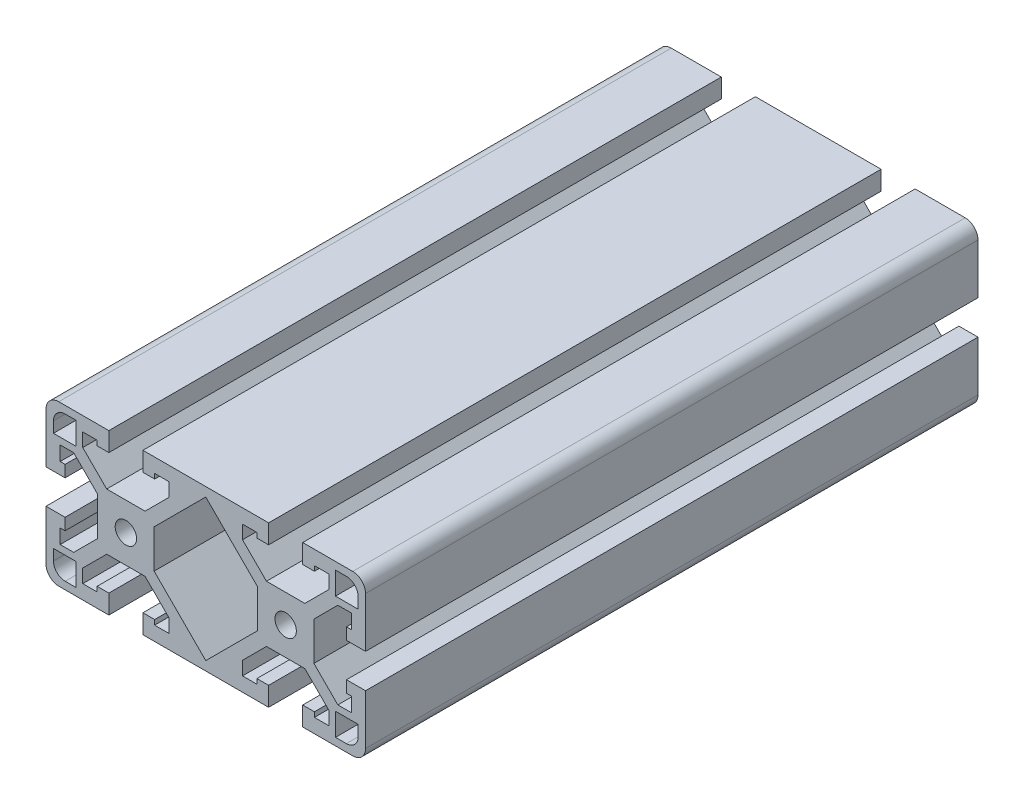
SolidWorks part; units mm, degrees
material "6061 Alloy"
ref_plane "Front Plane" through (0, 0, 0) normal (0, 0, 1) x (1, 0, 0)
ref_plane "Top Plane" through (0, 0, 0) normal (0, 1, 0) x (1, 0, 0)
ref_plane "Right Plane" through (0, 0, 0) normal (1, 0, 0) x (0, 0, -1)
sketch "Sketch1" plane through (0, 0, 0) normal (0, 0, 1) x (1, 0, 0)
  line L0 (-12.319, 4.5757) -> (-12.319, -4.5757)
  line L1 (0, 16.8947) -> (-12.319, 4.5757)
  line L2 (12.319, 4.5757) -> (0, 16.8947)
  line L3 (12.319, -4.5757) -> (12.319, 4.5757)
  line L4 (0, -16.8947) -> (12.319, -4.5757)
  line L5 (-12.319, -4.5757) -> (0, -16.8947)
  line L6 (-30.9372, 11.8872) -> (-30.9372, 17.272)
  line L7 (-36.322, 11.8872) -> (-30.9372, 11.8872)
  line L8 (-36.322, 14.478) -> (-36.322, 11.8872)
  line L9 (-30.9372, 17.272) -> (-33.528, 17.272)
  line L10 (-30.9372, -17.272) -> (-30.9372, -11.8872)
  line L11 (-33.528, -17.272) -> (-30.9372, -17.272)
  line L12 (-36.322, -11.8872) -> (-36.322, -14.478)
  line L13 (-30.9372, -11.8872) -> (-36.322, -11.8872)
  line L14 (36.322, -11.8872) -> (30.9372, -11.8872)
  line L15 (36.322, -14.478) -> (36.322, -11.8872)
  line L16 (30.9372, -17.272) -> (33.528, -17.272)
  line L17 (30.9372, -11.8872) -> (30.9372, -17.272)
  line L18 (30.9372, 17.272) -> (30.9372, 11.8872)
  line L19 (33.528, 17.272) -> (30.9372, 17.272)
  line L20 (36.322, 11.8872) -> (36.322, 14.478)
  line L21 (30.9372, 11.8872) -> (36.322, 11.8872)
  line L22 (-29.337, 12.4423) -> (-29.337, 15.6718)
  line L23 (-29.337, 15.6718) -> (-25.908, 15.6718)
  line L24 (-25.908, 15.6718) -> (-25.908, 14.5034)
  line L25 (-25.908, 14.5034) -> (-23.114, 14.5034)
  line L26 (-23.114, 14.5034) -> (-23.114, 19.05)
  line L27 (-23.114, 19.05) -> (-35.052, 19.05)
  line L28 (-38.1, 16.002) -> (-38.1, 4.064)
  line L29 (-38.1, 4.064) -> (-33.5534, 4.064)
  line L30 (-33.5534, 4.064) -> (-33.5534, 6.858)
  line L31 (-33.5534, 6.858) -> (-34.7218, 6.858)
  line L32 (-34.7218, 6.858) -> (-34.7218, 10.287)
  line L33 (-34.7218, 10.287) -> (-31.4923, 10.287)
  line L34 (-31.4923, 10.287) -> (-25.781, 4.5757)
  line L35 (-25.781, 4.5757) -> (-25.781, -4.5757)
  line L36 (-25.781, -4.5757) -> (-31.4923, -10.287)
  line L37 (-31.4923, -10.287) -> (-34.7218, -10.287)
  line L38 (-34.7218, -10.287) -> (-34.7218, -6.858)
  line L39 (-34.7218, -6.858) -> (-33.5534, -6.858)
  line L40 (-33.5534, -6.858) -> (-33.5534, -4.064)
  line L41 (-33.5534, -4.064) -> (-38.1, -4.064)
  line L42 (-38.1, -4.064) -> (-38.1, -16.002)
  line L43 (-35.052, -19.05) -> (-23.114, -19.05)
  line L44 (-23.114, -19.05) -> (-23.114, -14.5034)
  line L45 (-23.114, -14.5034) -> (-25.908, -14.5034)
  line L46 (-25.908, -14.5034) -> (-25.908, -15.6718)
  line L47 (-25.908, -15.6718) -> (-29.337, -15.6718)
  line L48 (-29.337, -15.6718) -> (-29.337, -12.4423)
  line L49 (-29.337, -12.4423) -> (-23.6257, -6.731)
  line L50 (-23.6257, -6.731) -> (-14.4743, -6.731)
  line L51 (-14.4743, -6.731) -> (-8.763, -12.4423)
  line L52 (-8.763, -12.4423) -> (-8.763, -15.6718)
  line L53 (-8.763, -15.6718) -> (-12.192, -15.6718)
  line L54 (-12.192, -15.6718) -> (-12.192, -14.5034)
  line L55 (-12.192, -14.5034) -> (-14.986, -14.5034)
  line L56 (-14.986, -14.5034) -> (-14.986, -19.05)
  line L57 (-14.986, -19.05) -> (14.986, -19.05)
  line L58 (14.986, -19.05) -> (14.986, -14.5034)
  line L59 (14.986, -14.5034) -> (12.192, -14.5034)
  line L60 (12.192, -14.5034) -> (12.192, -15.6718)
  line L61 (12.192, -15.6718) -> (8.763, -15.6718)
  line L62 (8.763, -15.6718) -> (8.763, -12.4423)
  line L63 (8.763, -12.4423) -> (14.4743, -6.731)
  line L64 (14.4743, -6.731) -> (23.6257, -6.731)
  line L65 (23.6257, -6.731) -> (29.337, -12.4423)
  line L66 (29.337, -12.4423) -> (29.337, -15.6718)
  line L67 (29.337, -15.6718) -> (25.908, -15.6718)
  line L68 (25.908, -15.6718) -> (25.908, -14.5034)
  line L69 (25.908, -14.5034) -> (23.114, -14.5034)
  line L70 (23.114, -14.5034) -> (23.114, -19.05)
  line L71 (23.114, -19.05) -> (35.052, -19.05)
  line L72 (38.1, -16.002) -> (38.1, -4.064)
  line L73 (38.1, -4.064) -> (33.5534, -4.064)
  line L74 (33.5534, -4.064) -> (33.5534, -6.858)
  line L75 (33.5534, -6.858) -> (34.7218, -6.858)
  line L76 (34.7218, -6.858) -> (34.7218, -10.287)
  line L77 (34.7218, -10.287) -> (31.4923, -10.287)
  line L78 (31.4923, -10.287) -> (25.781, -4.5757)
  line L79 (25.781, -4.5757) -> (25.781, 4.5757)
  line L80 (25.781, 4.5757) -> (31.4923, 10.287)
  line L81 (31.4923, 10.287) -> (34.7218, 10.287)
  line L82 (34.7218, 10.287) -> (34.7218, 6.858)
  line L83 (34.7218, 6.858) -> (33.5534, 6.858)
  line L84 (33.5534, 6.858) -> (33.5534, 4.064)
  line L85 (33.5534, 4.064) -> (38.1, 4.064)
  line L86 (38.1, 4.064) -> (38.1, 16.002)
  line L87 (35.052, 19.05) -> (23.114, 19.05)
  line L88 (23.114, 19.05) -> (23.114, 14.5034)
  line L89 (23.114, 14.5034) -> (25.908, 14.5034)
  line L90 (25.908, 14.5034) -> (25.908, 15.6718)
  line L91 (25.908, 15.6718) -> (29.337, 15.6718)
  line L92 (29.337, 15.6718) -> (29.337, 12.4423)
  line L93 (29.337, 12.4423) -> (23.6257, 6.731)
  line L94 (23.6257, 6.731) -> (14.4743, 6.731)
  line L95 (14.4743, 6.731) -> (8.763, 12.4423)
  line L96 (8.763, 12.4423) -> (8.763, 15.6718)
  line L97 (8.763, 15.6718) -> (12.192, 15.6718)
  line L98 (12.192, 15.6718) -> (12.192, 14.5034)
  line L99 (12.192, 14.5034) -> (14.986, 14.5034)
  line L100 (14.986, 14.5034) -> (14.986, 19.05)
  line L101 (14.986, 19.05) -> (-14.986, 19.05)
  line L102 (-14.986, 19.05) -> (-14.986, 14.5034)
  line L103 (-14.986, 14.5034) -> (-12.192, 14.5034)
  line L104 (-12.192, 14.5034) -> (-12.192, 15.6718)
  line L105 (-12.192, 15.6718) -> (-8.763, 15.6718)
  line L106 (-8.763, 15.6718) -> (-8.763, 12.4423)
  line L107 (-8.763, 12.4423) -> (-14.4743, 6.731)
  line L108 (-14.4743, 6.731) -> (-23.6257, 6.731)
  line L109 (-23.6257, 6.731) -> (-29.337, 12.4423)
  circle A0 centre (-19.05, 0) radius 2.5527
  circle A1 centre (19.05, 0) radius 2.5527
  arc A2 (-35.052, 19.05) -> (-38.1, 16.002) centre (-35.052, 16.002) ccw
  arc A3 (-38.1, -16.002) -> (-35.052, -19.05) centre (-35.052, -16.002) ccw
  arc A4 (35.052, -19.05) -> (38.1, -16.002) centre (35.052, -16.002) ccw
  arc A5 (38.1, 16.002) -> (35.052, 19.05) centre (35.052, 16.002) ccw
  arc A6 (-33.528, 17.272) -> (-36.322, 14.478) centre (-33.528, 14.478) ccw
  arc A7 (-36.322, -14.478) -> (-33.528, -17.272) centre (-33.528, -14.478) ccw
  arc A8 (33.528, -17.272) -> (36.322, -14.478) centre (33.528, -14.478) ccw
  arc A9 (36.322, 14.478) -> (33.528, 17.272) centre (33.528, 14.478) ccw
extrude "Boss-Extrude1" add sketch "Sketch1" along normal mid plane 146.05
